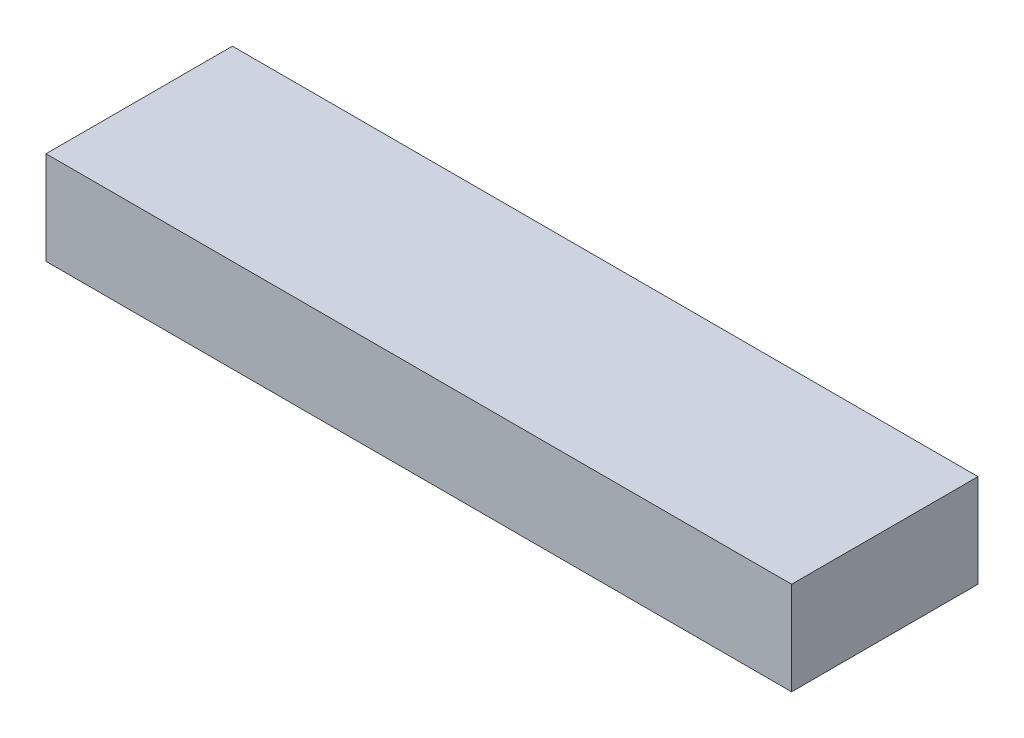
SolidWorks part; units mm, degrees
ref_plane "Front Plane" through (0, 0, 0) normal (0, 0, 1) x (1, 0, 0)
ref_plane "Top Plane" through (0, 0, 0) normal (0, 1, 0) x (1, 0, 0)
ref_plane "Right Plane" through (0, 0, 0) normal (1, 0, 0) x (0, 0, -1)
sketch "Sketch1" plane through (0, 0, 0) normal (0, 1, 0) x (1, 0, 0)
  line L1 (-74.5775, 17.9528) -> (45.4225, 17.9528)
  line L2 (-74.5775, 17.9528) -> (-74.5775, -12.0472)
  line L3 (-74.5775, -12.0472) -> (45.4225, -12.0472)
  line L4 (45.4225, 17.9528) -> (45.4225, -12.0472)
  dimension "D1" = 30
  dimension "D2" = 120
extrude "Boss-Extrude1" add sketch "Sketch1" along normal blind 15
